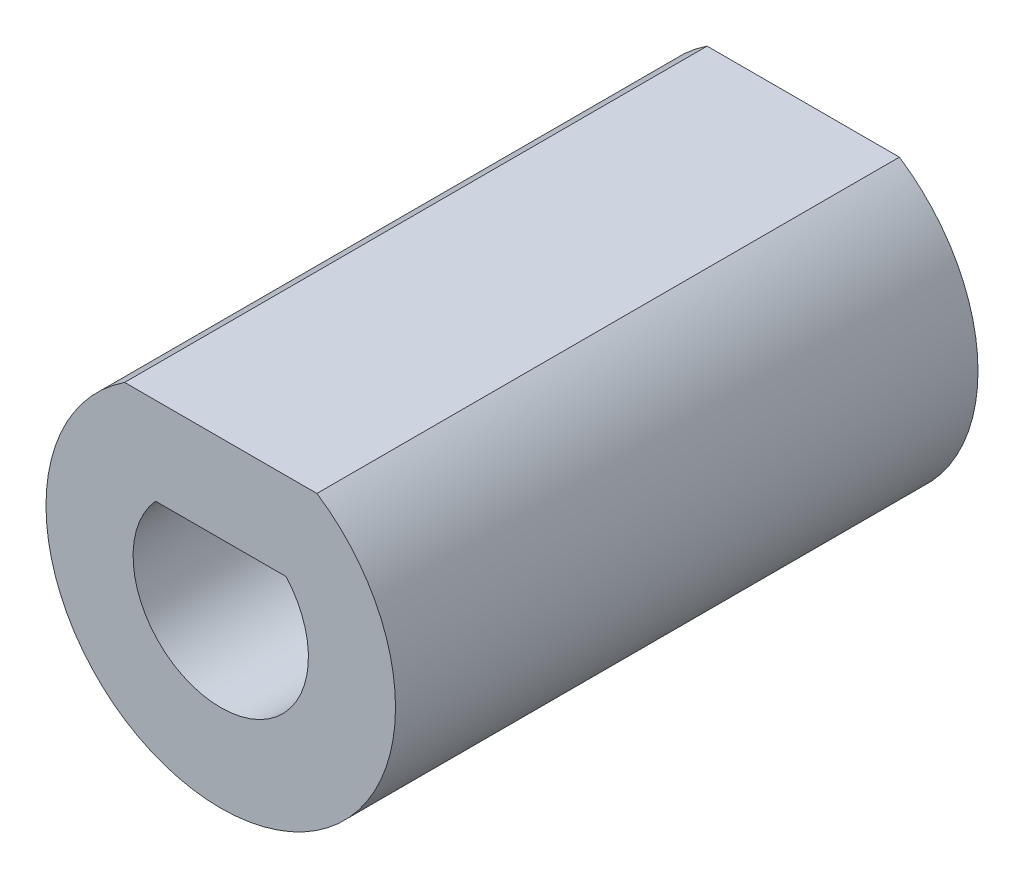
SolidWorks part; units mm, degrees
ref_plane "前视基准面" through (0, 0, 0) normal (0, 0, 1) x (1, 0, 0)
ref_plane "上视基准面" through (0, 0, 0) normal (0, 1, 0) x (1, 0, 0)
ref_plane "右视基准面" through (0, 0, 0) normal (1, 0, 0) x (0, 0, -1)
other "Configuration Table"
sketch "草图1" plane through (0, 0, 0) normal (0, 0, 1) x (1, 0, 0)
  circle A0 centre (0, 0) radius 3
  dimension "D1" = 6
extrude "凸台-拉伸1" add sketch "草图1" along normal blind 10
sketch "草图2" plane through (0, 0, 10) normal (0, 0, 1) x (1, 0, 0)
  line L0 (1.1203, 1.005) -> (-1.1203, 1.005)
  arc A0 (-1.1203, 1.005) -> (1.1203, 1.005) centre (0, 0) ccw
  dimension "D1" = 1.505
  dimension "D2" = 2.51
extrude "切除-拉伸1" cut sketch "草图2" against normal blind 10
sketch "草图3" plane through (0, 0, 0) normal (0, 0, -1) x (-1, 0, 0)
  line L0 (-1.6507, 2.505) -> (1.6507, 2.505)
  line L1 (-1.1203, 1.005) -> (1.1203, 1.005) construction
  circle A0 centre (0, 0) radius 3 construction
  arc A1 (1.6507, 2.505) -> (-1.6507, 2.505) centre (0, 0) ccw
  dimension "D1" = 1.5
extrude "切除-拉伸2" cut sketch "草图3" against normal blind 10
